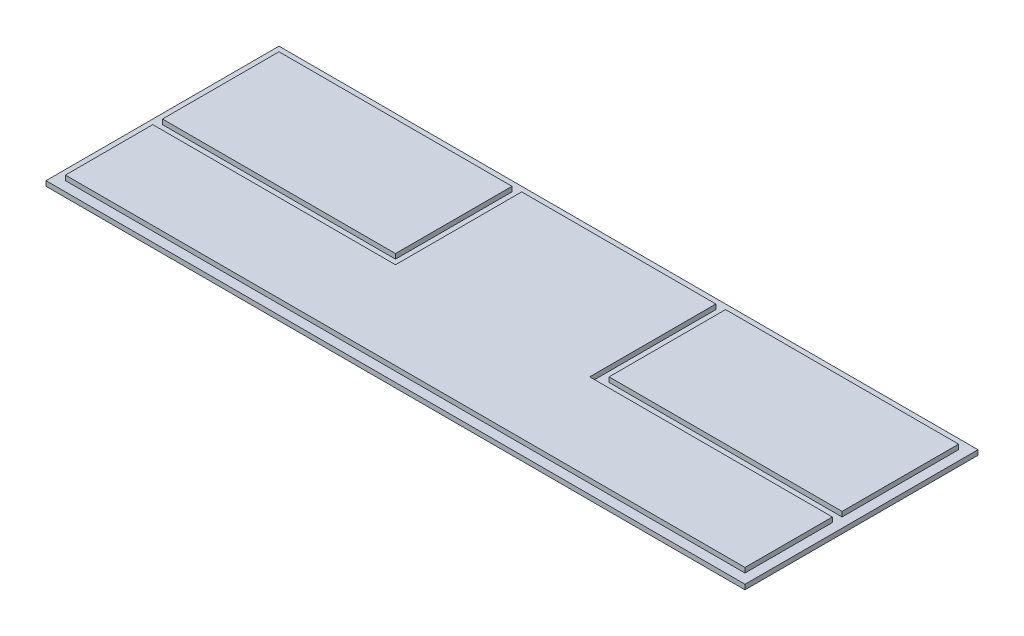
SolidWorks part; units mm, degrees
ref_plane "Front Plane" through (0, 0, 0) normal (0, 0, 1) x (1, 0, 0)
ref_plane "Top Plane" through (0, 0, 0) normal (0, 1, 0) x (1, 0, 0)
ref_plane "Right Plane" through (0, 0, 0) normal (1, 0, 0) x (0, 0, -1)
sketch "Sketch1" plane through (0, 0, 0) normal (0, 1, 0) x (1, 0, 0)
  line L1 (0, 0) -> (914.4, 0)
  line L2 (0, 0) -> (0, 304.8)
  line L3 (0, 304.8) -> (914.4, 304.8)
  line L4 (914.4, 0) -> (914.4, 304.8)
  dimension "D1" = 914.4
  dimension "D2" = 304.8
extrude "Boss-Extrude1" add sketch "Sketch1" along normal blind 12.7
sketch "Sketch2" plane through (0, 12.7, 0) normal (0, 1, 0) x (1, 0, 0)
  line L0 (330.2, 127) -> (12.7, 127)
  line L1 (317.5, 139.7) -> (12.7, 139.7)
  line L2 (0, 304.8) -> (0, 0)
  line L3 (596.9, 139.7) -> (901.7, 139.7)
  line L4 (12.7, 292.1) -> (12.7, 139.7)
  line L5 (596.9, 292.1) -> (901.7, 292.1)
  line L6 (12.7, 127) -> (12.7, 12.7)
  line L7 (914.4, 304.8) -> (914.4, 0)
  line L8 (12.7, 12.7) -> (901.7, 12.7)
  line L9 (901.7, 292.1) -> (901.7, 139.7)
  line L10 (0, 0) -> (914.4, 0)
  line L11 (901.7, 12.7) -> (901.7, 127)
  line L12 (901.7, 127) -> (584.2, 127)
  line L14 (0, 304.8) -> (914.4, 304.8)
  line L16 (12.7, 292.1) -> (317.5, 292.1)
  line L19 (596.9, 292.1) -> (596.9, 139.7)
  line L21 (584.2, 292.1) -> (584.2, 127)
  line L23 (317.5, 292.1) -> (317.5, 139.7)
  line L24 (330.2, 292.1) -> (584.2, 292.1)
  line L25 (330.2, 292.1) -> (330.2, 127)
  dimension "D2" = 152.4
  dimension "D3" = 152.4
  dimension "D4" = 12.7
  dimension "D5" = 304.8
  dimension "D6" = 12.7
  dimension "D7" = 12.7
  dimension "D8" = 12.7
  dimension "D9" = 304.8
  dimension "D10" = 12.7
  dimension "D11" = 12.7
  dimension "D12" = 12.7
  dimension "D13" = 12.7
  dimension "D14" = 12.7
extrude "Cut-Extrude1" cut sketch "Sketch2" against normal blind 6.35
